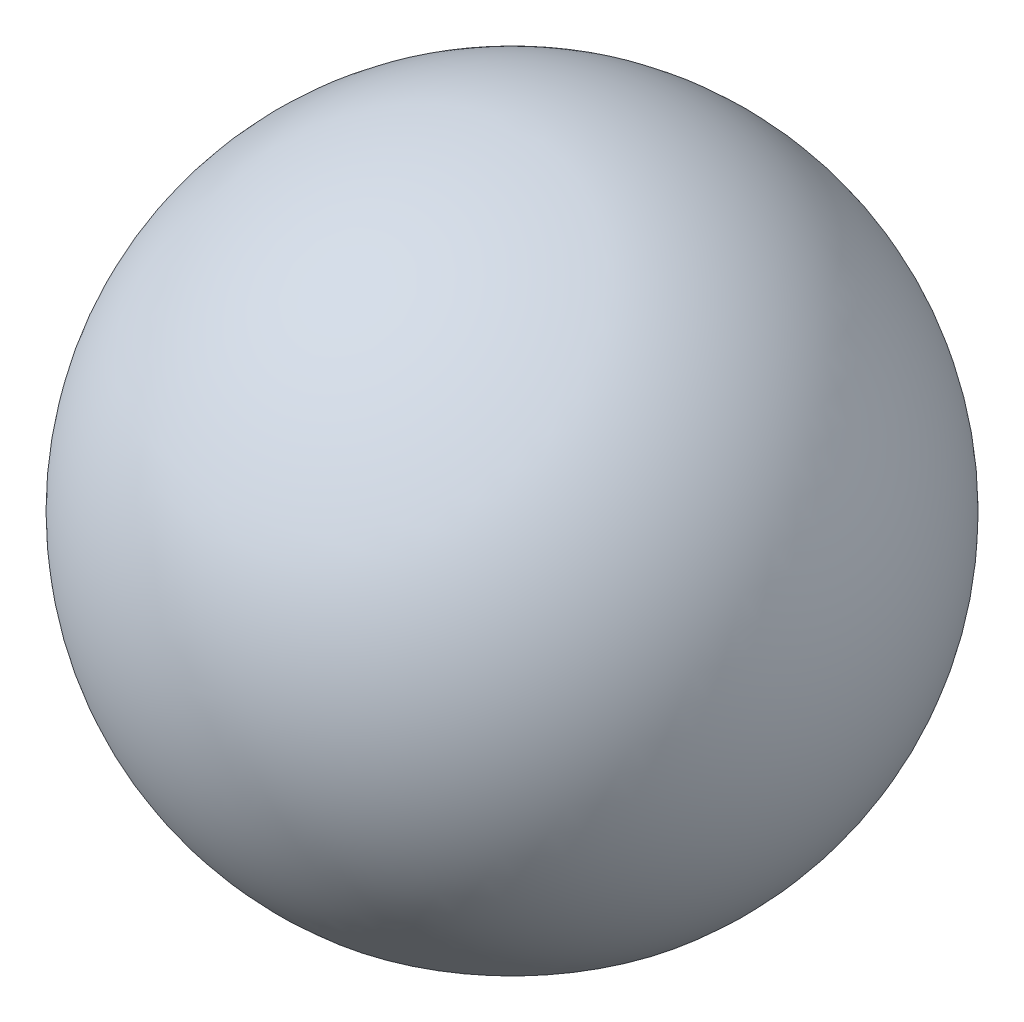
SolidWorks part; units mm, degrees
ref_plane "Front" through (0, 0, 0) normal (0, 0, 1) x (1, 0, 0)
ref_plane "Top" through (0, 0, 0) normal (0, 1, 0) x (1, 0, 0)
ref_plane "Right" through (0, 0, 0) normal (1, 0, 0) x (0, 0, -1)
other "Configuration Table"
sketch "Esquisse2" plane through (0, 0, 0) normal (1, 0, 0) x (0, 0, -1)
  line L0 (0, 0) -> (0, 25)
  arc A0 (0, 25) -> (0, 0) centre (0, 12.5) cw
  dimension "D1" = 25
revolve "Révolution1" add sketch "Esquisse2" angle 360 about L0
sketch "Esquisse3" plane through (0, 0, 0) normal (0, 1, 0) x (1, 0, 0)
  line L0 (-5.2, -3.95) -> (5.2, -3.95)
  line L1 (-5, -3.75) -> (5, -3.75)
  line L2 (-5, -3.75) -> (-5, 3.75)
  line L3 (-5, 3.75) -> (5, 3.75)
  line L4 (5, -3.75) -> (5, 3.75)
  line L5 (-5, -3.75) -> (5, 3.75) construction
  line L6 (-5, 3.75) -> (5, -3.75) construction
  line L7 (5.2, -3.95) -> (5.2, 3.95)
  line L8 (-5.2, 3.95) -> (5.2, 3.95)
  line L9 (-5.2, -3.95) -> (-5.2, 3.95)
  point P0 (0, 0)
  dimension "D1" = 7.5
  dimension "D2" = 10
  dimension "D3" = 0.2
extrude "Enlèv. mat.-Extru.1" cut sketch "Esquisse3" along normal blind 10 contours L1 L4 L3 L2 | L9 L0 L7 L8 L4 L1 L2 L3
sketch "Esquisse5" plane through (0, 0, 0) normal (0, 1, 0) x (1, 0, 0)
  line L1 (-10, 10) -> (10, 10)
  line L2 (-10, 10) -> (-10, -10)
  line L3 (-10, -10) -> (10, -10)
  line L4 (10, 10) -> (10, -10)
  line L5 (-10, 10) -> (10, -10) construction
  line L6 (-10, -10) -> (10, 10) construction
  point P0 (0, 0)
  dimension "D1" = 20
  dimension "D2" = 20
extrude "Enlèv. mat.-Extru.2" cut sketch "Esquisse5" along normal blind 3
